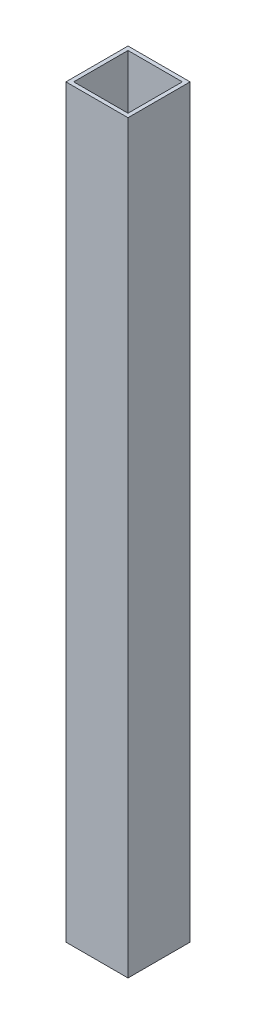
SolidWorks part; units mm, degrees
ref_plane "Front Plane" through (0, 0, 0) normal (0, 0, 1) x (1, 0, 0)
ref_plane "Top Plane" through (0, 0, 0) normal (0, 1, 0) x (1, 0, 0)
ref_plane "Right Plane" through (0, 0, 0) normal (1, 0, 0) x (0, 0, -1)
sketch "Sketch1" plane through (0, 0, 0) normal (0, 1, 0) x (1, 0, 0)
  line L1 (-12.7, 12.7) -> (12.7, 12.7)
  line L2 (-12.7, 12.7) -> (-12.7, -12.7)
  line L3 (-12.7, -12.7) -> (12.7, -12.7)
  line L4 (12.7, 12.7) -> (12.7, -12.7)
  line L5 (-12.7, 12.7) -> (12.7, -12.7) construction
  line L6 (-12.7, -12.7) -> (12.7, 12.7) construction
  line L7 (11.1125, -11.1125) -> (-11.1125, -11.1125)
  line L8 (11.1125, -11.1125) -> (11.1125, 11.1125)
  line L9 (11.1125, 11.1125) -> (-11.1125, 11.1125)
  line L10 (-11.1125, -11.1125) -> (-11.1125, 11.1125)
  line L11 (11.1125, -11.1125) -> (-11.1125, 11.1125) construction
  line L12 (11.1125, 11.1125) -> (-11.1125, -11.1125) construction
  point P0 (0, 0)
  point P6 (0, 0)
  dimension "D1" = 25.4
  dimension "D2" = 1.5875
extrude "Boss-Extrude1" add sketch "Sketch1" along normal blind 304.8
other "1in Square tube<1>"
